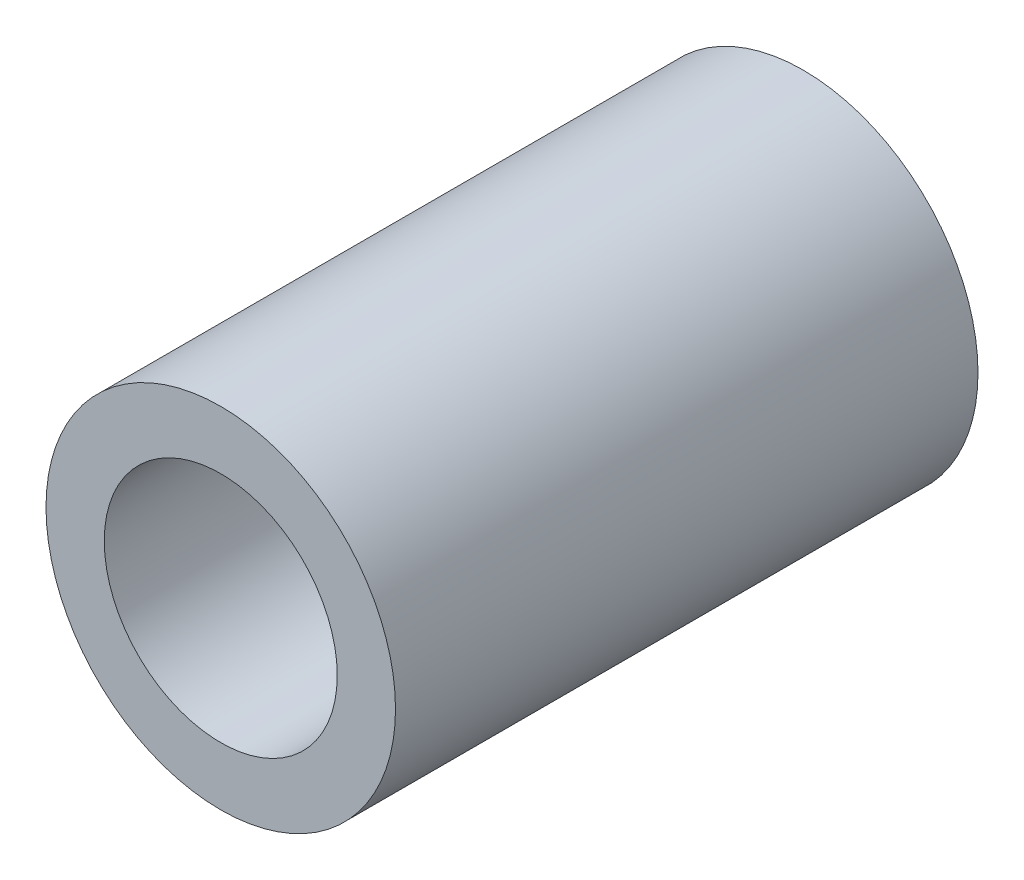
SolidWorks part; units mm, degrees
ref_plane "Front Plane" through (0, 0, 0) normal (0, 0, 1) x (1, 0, 0)
ref_plane "Top Plane" through (0, 0, 0) normal (0, 1, 0) x (1, 0, 0)
ref_plane "Right Plane" through (0, 0, 0) normal (1, 0, 0) x (0, 0, -1)
sketch "Sketch1" plane through (0, 0, 0) normal (0, 0, 1) x (1, 0, 0)
  circle A0 centre (0, 0) radius 30
  circle A1 centre (0, 0) radius 20
  dimension "D1" = 60
  dimension "D2" = 40
extrude "Boss-Extrude1" add sketch "Sketch1" along normal blind 100
